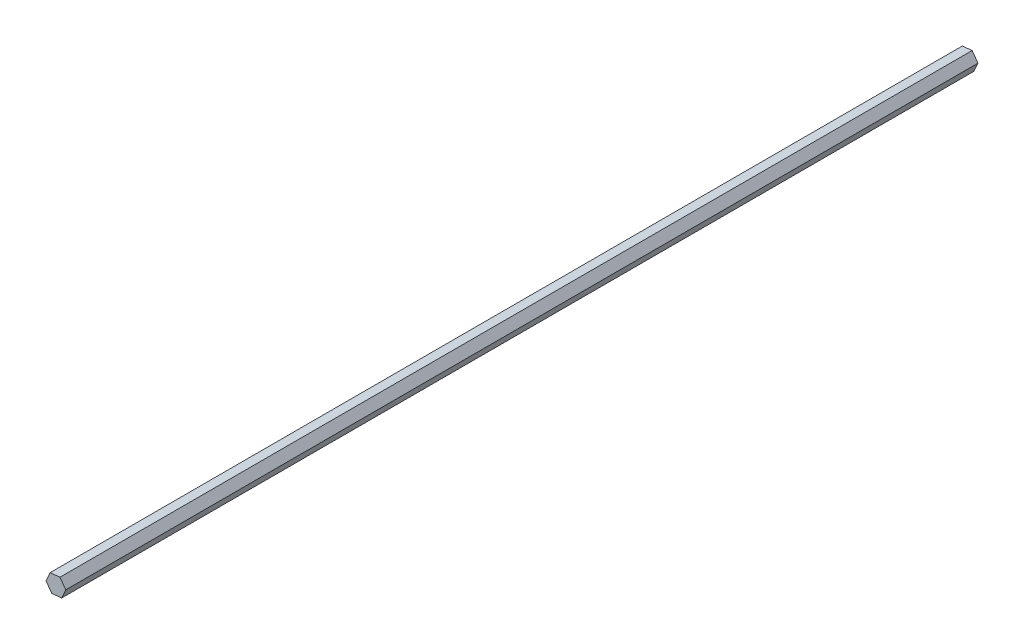
SolidWorks part; units mm, degrees
ref_plane "Front Plane" through (0, 0, 0) normal (0, 0, 1) x (1, 0, 0)
ref_plane "Top Plane" through (0, 0, 0) normal (0, 1, 0) x (1, 0, 0)
ref_plane "Right Plane" through (0, 0, 0) normal (1, 0, 0) x (0, 0, -1)
sketch "Sketch1" plane through (0, 0, 0) normal (0, 0, 1) x (1, 0, 0)
  line L1 (-4.3075, 5.9337) -> (-7.2925, -0.7635)
  line L2 (-7.2925, -0.7635) -> (-2.985, -6.6972)
  line L3 (-2.985, -6.6972) -> (4.3075, -5.9337)
  line L4 (4.3075, -5.9337) -> (7.2925, 0.7635)
  line L5 (7.2925, 0.7635) -> (2.985, 6.6972)
  line L6 (2.985, 6.6972) -> (-4.3075, 5.9337)
  circle A0 centre (0, 0) radius 6.35 construction
  dimension "D1" = 12.7
extrude "Boss-Extrude1" add sketch "Sketch1" along normal blind 673.1
